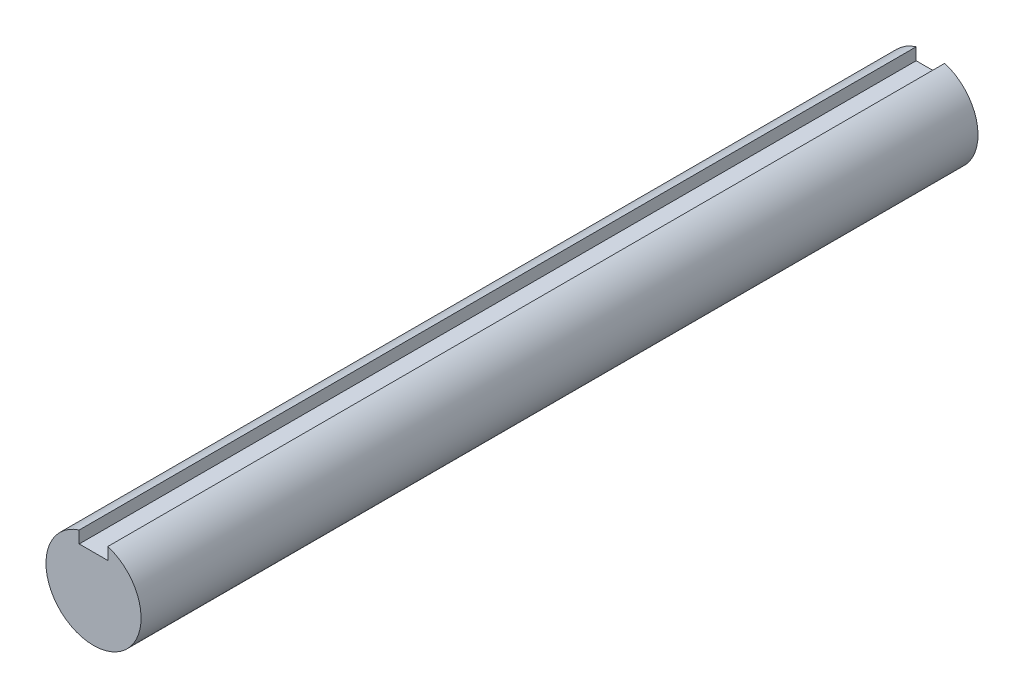
SolidWorks part; units mm, degrees
ref_plane "Front Plane" through (0, 0, 0) normal (0, 0, 1) x (1, 0, 0)
ref_plane "Top Plane" through (0, 0, 0) normal (0, 1, 0) x (1, 0, 0)
ref_plane "Right Plane" through (0, 0, 0) normal (1, 0, 0) x (0, 0, -1)
sketch "Sketch1" plane through (0, 0, 0) normal (1, 0, 0) x (0, 0, -1)
  line L0 (0, 0) -> (0, 3.9687) construction
  line L1 (-34.925, 3.9687) -> (34.925, 3.9688)
  line L2 (-34.925, 3.9687) -> (-34.925, -3.9688)
  line L3 (-34.925, -3.9688) -> (34.925, -3.9687)
  line L4 (34.925, 3.9688) -> (34.925, -3.9687)
  line L5 (-34.925, 3.9687) -> (34.925, -3.9687) construction
  line L6 (-34.925, -3.9688) -> (34.925, 3.9688) construction
  line L7 (0, 0) -> (0, -3.9688) construction
  line L8 (34.925, 3.9687) -> (-34.925, 3.9687) construction
  point P0 (0, 0)
  point P8 (-25.7969, 3.9687)
  point P10 (25.7969, 3.9687)
  point P11 (-22.7542, -3.9687)
  point P12 (24.3848, -3.9687)
  point P15 (0, 3.9687)
  dimension "Diameter" = 7.9375
  dimension "Length" = 69.85
  dimension "D1" = 9.1281
  dimension "D2" = 9.1281
  dimension "D3" = 12.1708
  dimension "D4" = 10.5402
  dimension "Key Length" = 69.85
sketch "Sketch2" plane through (0, 0, 0) normal (0, 0, 1) x (1, 0, 0)
  line L0 (0, 0) -> (0, 3.9687) construction
  line L2 (1.1938, 2.7749) -> (-1.1938, 2.7749)
  line L3 (1.1938, 2.7749) -> (1.1938, 3.9687)
  line L4 (1.1938, 3.9687) -> (-1.1938, 3.9687)
  line L5 (-1.1938, 2.7749) -> (-1.1938, 3.9687)
  line L6 (1.1938, 2.7749) -> (-1.1938, 3.9687) construction
  line L7 (1.1938, 3.9687) -> (-1.1938, 2.7749) construction
  circle A0 centre (0, 0) radius 3.9687
  point P3 (0, 3.3718)
  dimension "Keyway Width" = 2.3876
  dimension "Keyway Depth" = 1.1938
sketch "Sketch3" plane through (0, 0, 0) normal (0, 0, 1) x (1, 0, 0)
  line L1 (-1.1938, 2.7749) -> (-1.1938, 3.9687) construction
  line L2 (1.1938, 2.7749) -> (-1.1938, 2.7749) construction
  line L3 (1.1938, 2.7749) -> (1.1938, 3.9687) construction
  line L5 (-1.1938, 2.7749) -> (-1.1938, 3.7849)
  line L6 (1.1938, 2.7749) -> (-1.1938, 2.7749)
  line L7 (1.1938, 2.7749) -> (1.1938, 3.7849)
  arc A1 (-1.1938, 3.7849) -> (1.1938, 3.7849) centre (0, 0) ccw
  circle A2 centre (0, 0) radius 3.9687 construction
extrude "Boss-Extrude1" add sketch "Sketch3" along normal up to vertex (34.925 mm away) and the other way up to vertex (34.925 mm away) up to point (0, 3.9687, 34.925) other way up to point (0, 3.9688, -34.925)
chamfer "Chamfer1" [suppressed] distance 0.0794 angle 45
equation "\"D2@Sketch1\"=1.15*\"Diameter@Sketch1\""
equation "\"D1@Sketch1\"=\"D2@Sketch1\""
equation "\"D3@Sketch1\"=\"D2@Sketch1\"*4/3"
equation "\"D4@Sketch1\"=\"D2@Sketch1\"/(tan(.5236*180/pi)*2)*4/3"
equation "\"D1@Chamfer1\"=\"Diameter@Sketch1\"*.01"
equation "\"Key Length@Sketch1\"=\"Length@Sketch1\""
